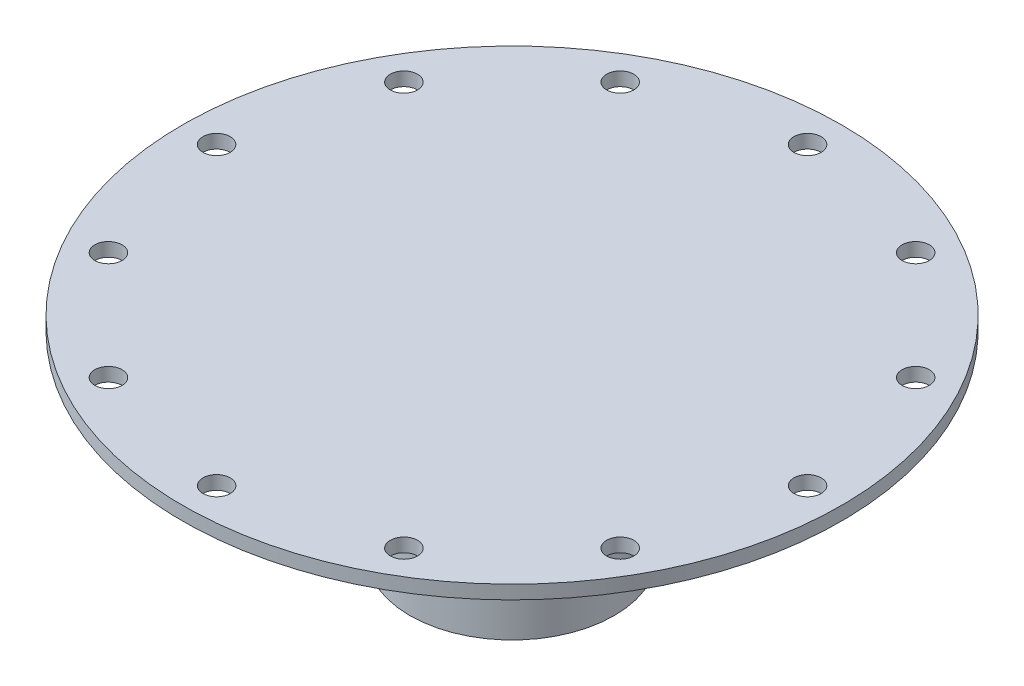
SolidWorks part; units mm, degrees
ref_plane "Front Plane" through (0, 0, 0) normal (0, 0, 1) x (1, 0, 0)
ref_plane "Top Plane" through (0, 0, 0) normal (0, 1, 0) x (1, 0, 0)
ref_plane "Right Plane" through (0, 0, 0) normal (1, 0, 0) x (0, 0, -1)
sketch "Sketch1" plane through (0, 0, 0) normal (1, 0, 0) x (0, 0, -1)
  line L0 (0, 0) -> (0, -40)
  line L1 (0, -40) -> (22.5, -40)
  line L2 (22.5, -40) -> (22.5, 0)
  line L3 (22.5, 0) -> (50, 0)
  line L4 (50, 0) -> (50, 6)
  line L5 (50, 6) -> (0, 6)
  line L6 (0, 6) -> (0, 0)
  dimension "D1" = 22.5
  dimension "D2" = 50
  dimension "D3" = 6
  dimension "D4" = 40
revolve "Revolve1" add sketch "Sketch1" angle 360 about L6
sketch "Sketch2" plane through (0, 0, 0) normal (0, 1, 0) x (1, 0, 0)
  line L0 (0, 0) -> (0, -65) construction
  circle A0 centre (0, 0) radius 72.5
  circle A1 centre (0, -65) radius 3
  circle A5 centre (-32.5, -56.2917) radius 3
  circle A6 centre (-56.2917, -32.5) radius 3
  circle A7 centre (-65, 0) radius 3
  circle A8 centre (-56.2917, 32.5) radius 3
  circle A9 centre (-32.5, 56.2917) radius 3
  circle A10 centre (0, 65) radius 3
  circle A11 centre (32.5, 56.2917) radius 3
  circle A12 centre (56.2917, 32.5) radius 3
  circle A13 centre (65, 0) radius 3
  circle A14 centre (56.2917, -32.5) radius 3
  circle A15 centre (32.5, -56.2917) radius 3
  point P29 (0, 0)
  dimension "D1" = 6
  dimension "D3" = 145
  dimension "D2" = 65
  dimension "D4" = 12
extrude "Boss-Extrude1" add sketch "Sketch2" against normal blind 3 from surface at 6 starting at face at (0, 6, 50)
